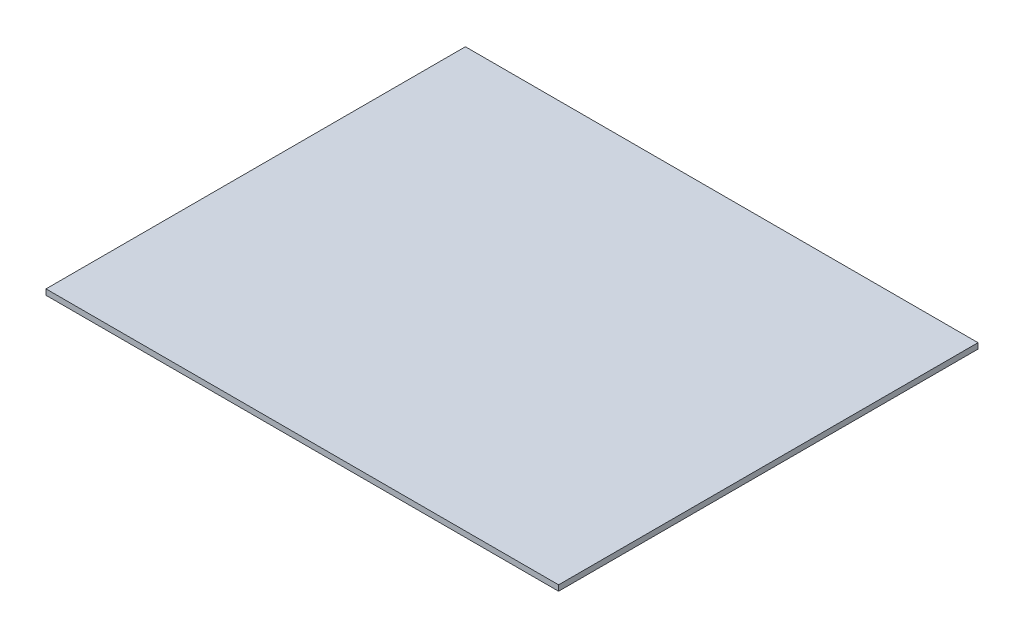
SolidWorks part; units mm, degrees
material "Maple"
ref_plane "Front Plane" through (0, 0, 0) normal (0, 0, 1) x (1, 0, 0)
ref_plane "Top Plane" through (0, 0, 0) normal (0, 1, 0) x (1, 0, 0)
ref_plane "Right Plane" through (0, 0, 0) normal (1, 0, 0) x (0, 0, -1)
sketch "Sketch1" plane through (0, 0, 0) normal (0, 1, 0) x (1, 0, 0)
  line L1 (550, -450) -> (-550, -450)
  line L2 (550, -450) -> (550, 450)
  line L3 (550, 450) -> (-550, 450)
  line L4 (-550, -450) -> (-550, 450)
  line L5 (550, -450) -> (-550, 450) construction
  line L6 (550, 450) -> (-550, -450) construction
  point P0 (0, 0)
  dimension "D1" = 1100
  dimension "D2" = 900
extrude "Boss-Extrude1" add sketch "Sketch1" along normal mid plane 12
equation "\"M5_tap\"=4.2mm\t\t\t\t\t\t\t' Below you can do mesurements as follows: cm, mm, ft, in, m, "
equation "\"M5_clearence\"=5.5mm"
equation "\"M6_tap\"=5mm"
equation "\"M6_clearence\"=6.6mm"
equation "\"work_area_width\"=1100mm"
equation "\"work_area_depth\"=900mm"
equation "\"D1@Sketch1\"=\"work_area_width\""
equation "\"D2@Sketch1\"=\"work_area_depth\""
